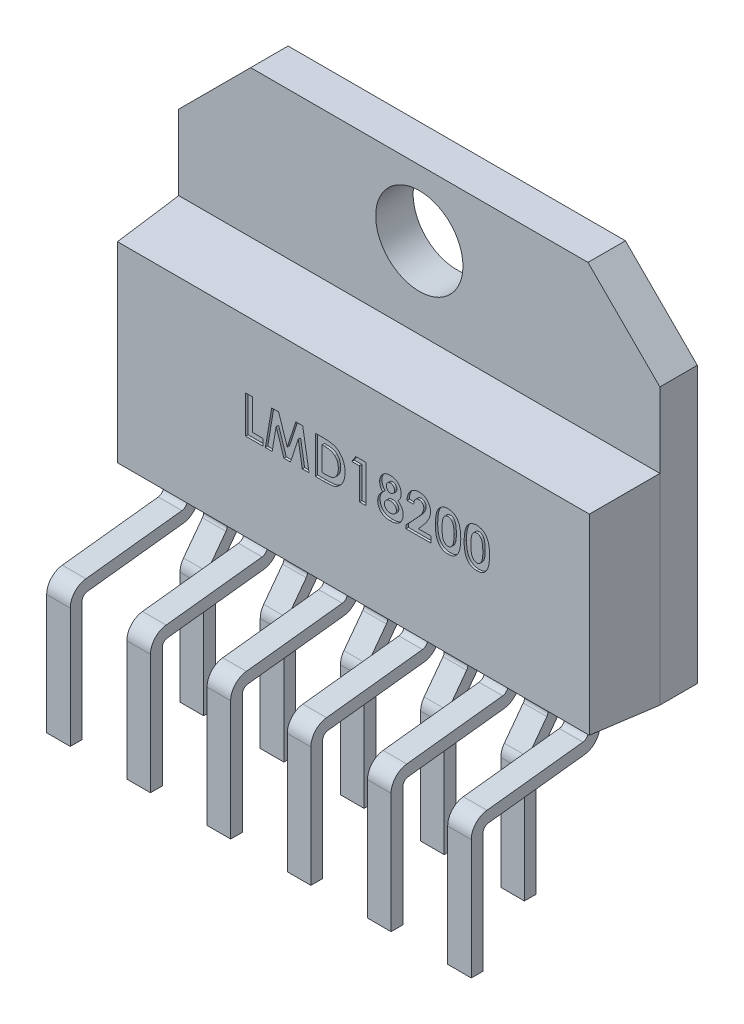
SolidWorks part; units mm, degrees
ref_plane "Front" through (0, 0, 0) normal (0, 0, 1) x (1, 0, 0)
ref_plane "Top" through (0, 0, 0) normal (0, 1, 0) x (1, 0, 0)
ref_plane "Right" through (0, 0, 0) normal (1, 0, 0) x (0, 0, -1)
sketch "Sketch1" plane through (0, 0, 0) normal (1, 0, 0) x (0, 0, -1)
  line L0 (0, 2.79) -> (0, -11.942)
  line L1 (0, 2.79) -> (-1.5875, 2.79)
  line L2 (-1.5875, 2.79) -> (-1.5875, -11.942)
  line L5 (0, -11.942) -> (-1.5875, -11.942)
  dimension "D1" = 2.79
  dimension "D2" = 14.732
  dimension "D3" = 1.5875
extrude "Extrude2" add sketch "Sketch1" along normal mid plane 20.3962
sketch "Sketch4" plane through (0, 0, 1.5875) normal (0, 0, 1) x (1, 0, 0)
  line L0 (10.1981, -11.942) -> (-10.1981, -11.942) construction
  circle A0 centre (0, 0) radius 1.85
  dimension "D1" = 3.7
  dimension "D2" = 11.942
extrude "Cut-Extrude3" cut sketch "Sketch4" against normal through all
chamfer "Chamfer2" distance 3.048 angle 45 2 edges at (-10.1981, 2.79, 0.7937) (10.1981, 2.79, 0.7937)
sketch "Sketch5" plane through (0, 0, 1.5875) normal (0, 0, 1) x (1, 0, 0)
  line L0 (-10.1981, -0.258) -> (-10.1981, -11.942) construction
  line L1 (-10.1981, -3.433) -> (10.1981, -3.433)
  line L2 (-10.1981, -3.433) -> (-10.1981, -11.942)
  line L3 (-10.1981, -11.942) -> (10.1981, -11.942)
  line L4 (10.1981, -3.433) -> (10.1981, -11.942)
  dimension "D1" = 8.509
extrude "Extrude3" add sketch "Sketch5" along normal blind 2.794 draft 4
ref_plane "LED Plane1" through (0, -11.43, 0) normal (0, 1, 0) x (-1, 0, 0)
sketch "Sketch6" plane through (0, -11.43, 0) normal (0, 1, 0) x (-1, 0, 0)
  line L0 (-10.1981, 0) -> (-10.1981, 1.5875) construction
  line L1 (-9.1081, 3.04) -> (-8.1081, 3.04)
  line L2 (-9.1081, 3.04) -> (-9.1081, 3.54)
  line L3 (-9.1081, 3.54) -> (-8.1081, 3.54)
  line L4 (-8.1081, 3.04) -> (-8.1081, 3.54)
  line L5 (-7.1501, 0) -> (-10.1981, 0) construction
  dimension "D1" = 1
  dimension "D2" = 0.5
  dimension "D3" = 1.09
  dimension "D4" = 3.04
ref_plane "Plane3" through (8.6081, 0, 0) normal (1, 0, 0) x (0, 0, -1)
sketch "Sketch8" plane through (8.6081, 0, 0) normal (1, 0, 0) x (0, 0, -1)
  line L0 (-3.29, -11.43) -> (-3.29, -12.5083)
  line L2 (-3.04, -11.43) -> (-3.54, -11.43) construction
  line L3 (-3.7328, -13.005) -> (-7.8002, -13.4733)
  line L6 (-8.243, -13.97) -> (-8.243, -19.05)
  arc A0 (-7.8002, -13.4733) -> (-8.243, -13.97) centre (-7.743, -13.97) ccw
  arc A1 (-3.29, -12.5083) -> (-3.7328, -13.005) centre (-3.79, -12.5083) cw
  point P10 (-8.243, -13.5243)
  point P14 (-3.29, -12.954)
  dimension "D5" = 0.5
  dimension "D4" = 5.08
  dimension "D1" = 1.524
  dimension "D2" = 4.953
  dimension "D3" = 7.62
sweep "Sweep1" add profiles "Sketch6" path "Sketch8"
pattern_linear "LPattern1" count 6 spacing 3.4 along (-1, 0, 0) of "Sweep1"
sketch "Sketch9" plane through (0, -11.43, 0) normal (0, 1, 0) x (-1, 0, 0)
  line L1 (-7.4081, 3.04) -> (-6.4081, 3.04)
  line L2 (-7.4081, 3.04) -> (-7.4081, 3.54)
  line L3 (-7.4081, 3.54) -> (-6.4081, 3.54)
  line L4 (-6.4081, 3.04) -> (-6.4081, 3.54)
  line L5 (-8.6081, 2.8216) -> (-8.6081, -2.8216) construction
  line L7 (-5.7081, 3.04) -> (-4.7081, 3.04) construction
  dimension "D1" = 1
  dimension "D2" = 0.5
  dimension "D3" = 1.2
ref_plane "Plane4" through (6.9081, 0, 0) normal (1, 0, 0) x (0, 0, -1)
sketch "Sketch10" plane through (6.9081, 0, 0) normal (1, 0, 0) x (0, 0, -1)
  line L0 (-3.29, -11.43) -> (-3.29, -12.6057)
  line L1 (-3.04, -11.43) -> (-3.54, -11.43) construction
  line L2 (-7.993, -13.97) -> (-7.993, -19.05) construction
  line L3 (-3.3891, -12.9045) -> (-4.1909, -13.9806)
  line L4 (-4.29, -14.2794) -> (-4.29, -19.05)
  arc A0 (-4.1909, -13.9806) -> (-4.29, -14.2794) centre (-3.79, -14.2794) ccw
  arc A1 (-3.29, -12.6057) -> (-3.3891, -12.9045) centre (-3.79, -12.6057) cw
  point P12 (-4.29, -14.1136)
  point P15 (-3.29, -12.7715)
  dimension "D5" = 0.5
  dimension "D3" = 3.703
sweep "Sweep2" add profiles "Sketch9" path "Sketch10"
pattern_linear "LPattern2" count 5 spacing 3.4 along (-1, 0, 0) of "Sweep2"
sketch "Sketch12" plane through (0, -19.05, 0) normal (0, -1, 0) x (1, 0, 0)
  line L0 (0.1081, 4.54) -> (0.1081, 4.29) construction
  line L1 (-0.3919, 4.54) -> (0.6081, 4.54) construction
  line L2 (0.1081, 4.29) -> (0.1081, 4.04) construction
  line L3 (0.6081, 4.04) -> (-0.3919, 4.04) construction
  circle A0 centre (0.1081, 4.29) radius 0.2171
extrude "Extrude4" cut sketch "Sketch12" against normal blind 2.54
sketch "Sketch11" plane through (0, 0, 4.3815) normal (0, 0, 1) x (1, 0, 0)
  text T0 "<b>LMD18200</b>" font "Century Gothic" height in points 6
extrude "Cut-Extrude4" cut sketch "Sketch11" against normal blind 0.1
